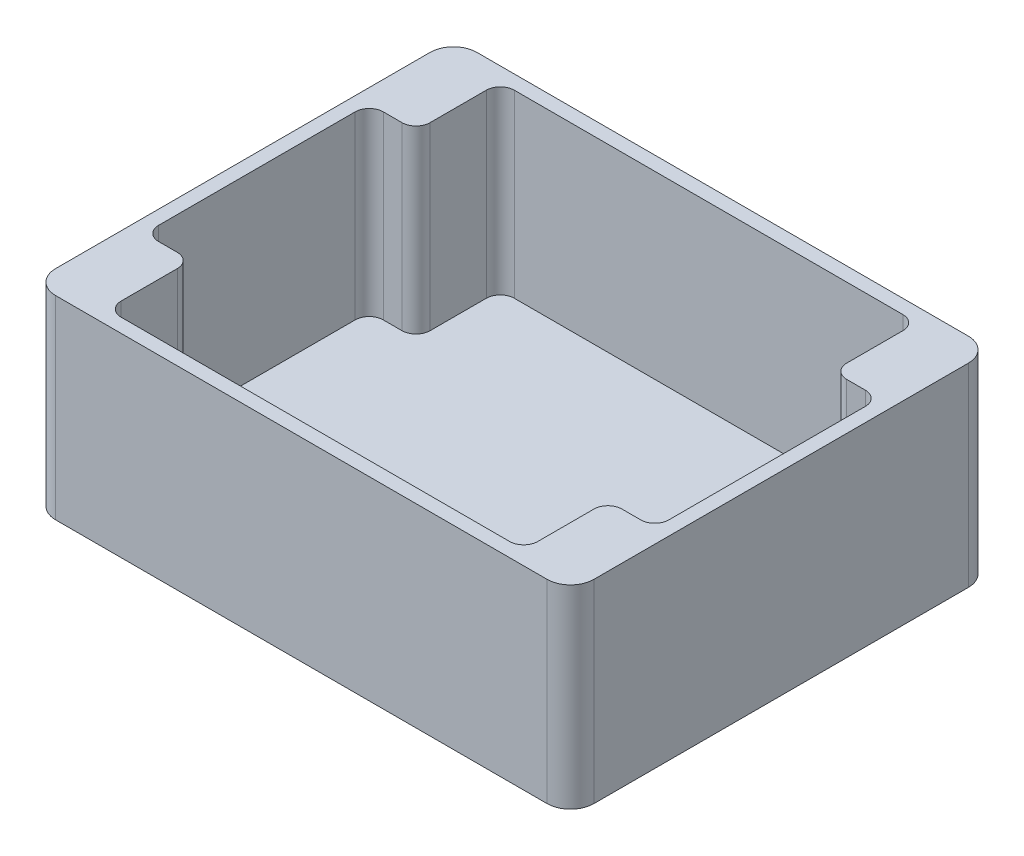
SolidWorks part; units mm, degrees
material "ABS"
ref_plane "Front Plane" through (0, 0, 0) normal (0, 0, 1) x (1, 0, 0)
ref_plane "Top Plane" through (0, 0, 0) normal (0, 1, 0) x (1, 0, 0)
ref_plane "Right Plane" through (0, 0, 0) normal (1, 0, 0) x (0, 0, -1)
sketch "Sketch1" plane through (0, 0, 0) normal (0, 1, 0) x (1, 0, 0)
  line L1 (0, 0) -> (115, 0)
  line L2 (0, 0) -> (0, 90)
  line L3 (0, 90) -> (115, 90)
  line L4 (115, 0) -> (115, 90)
  dimension "D1" = 115
  dimension "D2" = 90
extrude "Boss-Extrude1" add sketch "Sketch1" along normal blind 41.5
sketch "Sketch3" plane through (0, 41.5, 0) normal (0, 1, 0) x (1, 0, 0)
  line L14 (112, 3) -> (112, 87)
  line L15 (3, 3) -> (112, 3)
  line L16 (3, 87) -> (3, 3)
  line L17 (112, 87) -> (3, 87)
  line L18 (112, 3) -> (112, 87)
  line L19 (3, 3) -> (112, 3)
  line L20 (3, 87) -> (3, 3)
  line L21 (112, 87) -> (3, 87)
  dimension "D1" = 3
extrude "Cut-Extrude1" cut sketch "Sketch3" against normal offset from surface (38.5 mm away) 3 up to face at (57.5, 0, -45)
sketch "Sketch4" plane through (0, 3, 0) normal (0, 1, 0) x (1, 0, 0)
  line L0 (57.5, 87) -> (57.5, 3) construction
  line L1 (3, 87) -> (13, 87)
  line L2 (3, 87) -> (3, 69)
  line L3 (3, 69) -> (13, 69)
  line L4 (13, 87) -> (13, 69)
  line L5 (112, 87) -> (3, 87) construction
  line L6 (3, 3) -> (112, 3) construction
  line L7 (3, 45) -> (112, 45) construction
  line L8 (3, 87) -> (3, 3) construction
  line L9 (112, 3) -> (112, 87) construction
  line L10 (112, 69) -> (102, 69)
  line L11 (102, 87) -> (102, 69)
  line L12 (112, 87) -> (102, 87)
  line L13 (112, 87) -> (112, 69)
  line L14 (112, 3) -> (112, 21)
  line L15 (112, 3) -> (102, 3)
  line L16 (102, 3) -> (102, 21)
  line L17 (112, 21) -> (102, 21)
  line L18 (3, 21) -> (13, 21)
  line L19 (13, 3) -> (13, 21)
  line L20 (3, 3) -> (13, 3)
  line L21 (3, 3) -> (3, 21)
  dimension "D1" = 10
  dimension "D2" = 18
extrude "Boss-Extrude2" add sketch "Sketch4" along normal up to surface (38.5 mm away) up to face at (57.5, 41.5, -45)
fillet "Fillet1" radius 3 12 edges at (112, 22.25, -21) (102, 22.25, -21) (102, 22.25, -3) (13, 22.25, -3) (3, 22.25, -21) (13, 22.25, -21) (112, 22.25, -69) (102, 22.25, -69) (102, 22.25, -87) (13, 22.25, -87) (3, 22.25, -69) (13, 22.25, -69)
fillet "Fillet2" radius 5 4 edges at (115, 20.75, 0) (0, 20.75, 0) (115, 20.75, -90) (0, 20.75, -90)
